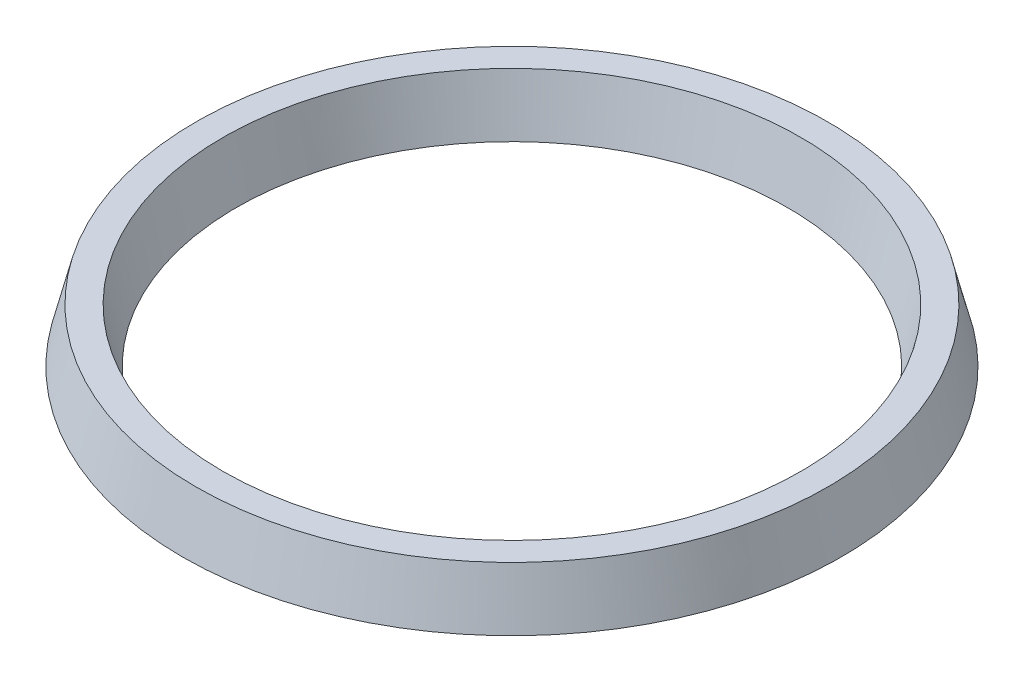
SolidWorks part; units mm, degrees
ref_plane "Front Plane" through (0, 0, 0) normal (0, 0, 1) x (1, 0, 0)
ref_plane "Top Plane" through (0, 0, 0) normal (0, 1, 0) x (1, 0, 0)
ref_plane "Right Plane" through (0, 0, 0) normal (1, 0, 0) x (0, 0, -1)
sketch "Sketch1" plane through (0, 0, 0) normal (1, 0, 0) x (0, 0, -1)
  line L0 (0, 0) -> (0, -19114.8632) construction
  line L1 (0, 0) -> (19114.8632, 0) construction
  line L2 (67.31, 3.5537) -> (67.31, -19111.3095) construction
  line L3 (64.31, 6) -> (70.31, 6)
  line L4 (70.31, 6) -> (73.31, -6)
  line L5 (73.31, -6) -> (70.31, -6)
  line L6 (61.31, -6) -> (64.31, -6)
  line L7 (64.31, 6) -> (61.31, -6)
  line L8 (64.31, -6) -> (65.4462, -1.4552)
  line L9 (69.1738, -1.4552) -> (70.31, -6)
  arc A0 (65.4462, -1.4552) -> (69.1738, -1.4552) centre (67.31, -1.9212) cw
  point P10 (67.31, 6)
  dimension "D1" = 146.62
  dimension "D2" = 140.62
  dimension "D3" = 6
  dimension "D4" = 3
  dimension "D5" = 12
  dimension "D6" = 12
  dimension "D7" = 6
revolve "Revolve1" add sketch "Sketch1" angle 360 about L0
